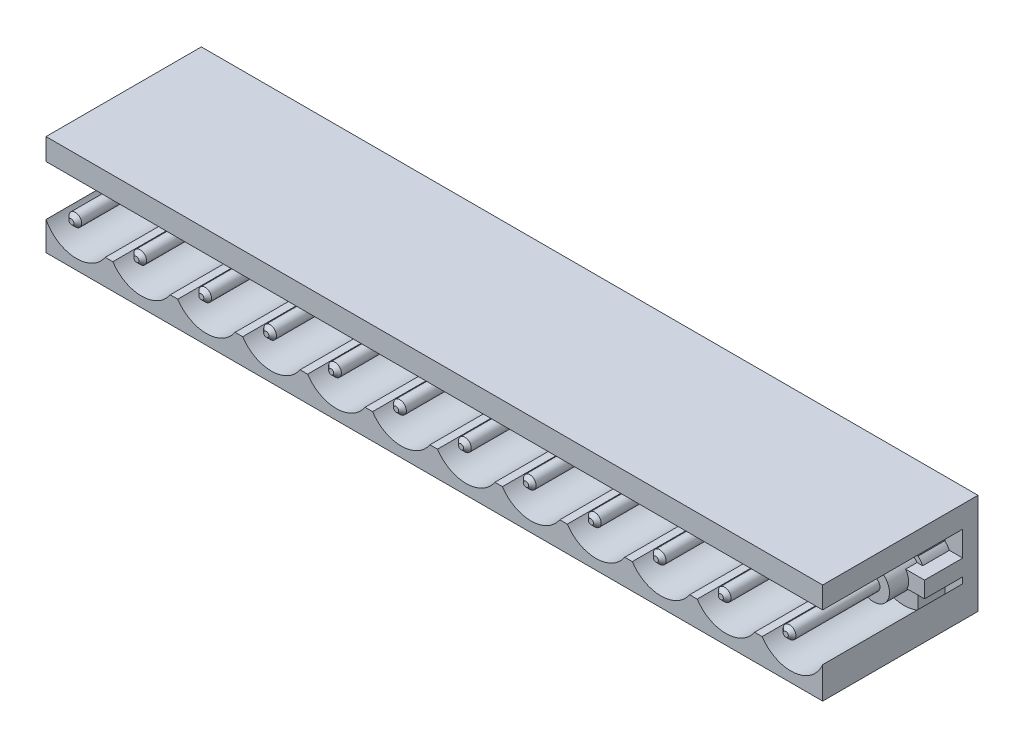
SolidWorks part; units mm, degrees
ref_plane "Front Plane" through (0, 0, 0) normal (0, 0, 1) x (1, 0, 0)
ref_plane "Top Plane" through (0, 0, 0) normal (0, 1, 0) x (1, 0, 0)
ref_plane "Right Plane" through (0, 0, 0) normal (1, 0, 0) x (0, 0, -1)
sketch "Sketch1" plane through (0, 0, 0) normal (1, 0, 0) x (0, 0, -1)
  line L1 (-6.1, 3.95) -> (6.1, 3.95)
  line L2 (-6.1, 3.95) -> (-6.1, -3.95)
  line L3 (-6.1, -3.95) -> (6.1, -3.95)
  line L4 (6.1, 3.95) -> (6.1, -3.95)
  line L5 (-6.1, 3.95) -> (6.1, -3.95) construction
  line L6 (-6.1, -3.95) -> (6.1, 3.95) construction
  point P0 (0, 0)
  dimension "D1" = 12.2
  dimension "D2" = 7.9
extrude "Boss-Extrude1" add sketch "Sketch1" along normal mid plane 61
sketch "Sketch2" plane through (0, 0, 6.1) normal (0, 0, 1) x (1, 0, 0)
  line L0 (30.5, -3.95) -> (-30.5, -3.95) construction
  line L1 (30.5, 3.95) -> (30.5, -3.95) construction
  line L2 (30.5, 3.95) -> (-30.5, 3.95) construction
  line L5 (25.3, 2.25) -> (30.7, 2.25)
  line L6 (30.7, -0.45) -> (30.7, 2.25)
  line L8 (20.2, 2.25) -> (25.6, 2.25)
  line L11 (15.1, 2.25) -> (20.5, 2.25)
  line L14 (10, 2.25) -> (15.4, 2.25)
  line L17 (4.9, 2.25) -> (10.3, 2.25)
  line L20 (-0.2, 2.25) -> (5.2, 2.25)
  line L23 (-5.3, 2.25) -> (0.1, 2.25)
  line L26 (-10.4, 2.25) -> (-5, 2.25)
  line L29 (-15.5, 2.25) -> (-10.1, 2.25)
  line L32 (-20.6, 2.25) -> (-15.2, 2.25)
  line L35 (-25.7, 2.25) -> (-20.3, 2.25)
  line L37 (-30.8, -0.45) -> (-30.8, 2.25)
  line L38 (-30.8, 2.25) -> (-25.4, 2.25)
  line L40 (-25.8467, -1.9375) -> (-25.2533, -1.9375)
  line L41 (-25.4, -0.45) -> (-25.4, 2.25) [skipped]
  line L42 (-20.7467, -1.9375) -> (-20.1533, -1.9375)
  line L43 (-20.3, -0.45) -> (-20.3, 2.25) [skipped]
  line L44 (-15.6467, -1.9375) -> (-15.0533, -1.9375)
  line L45 (-15.2, -0.45) -> (-15.2, 2.25) [skipped]
  line L46 (-10.5467, -1.9375) -> (-9.9533, -1.9375)
  line L47 (-10.1, -0.45) -> (-10.1, 2.25) [skipped]
  line L48 (-5.4467, -1.9375) -> (-4.8533, -1.9375)
  line L49 (20.5, -0.45) -> (20.5, 2.25) [skipped]
  line L50 (25.6, -0.45) -> (25.6, 2.25) [skipped]
  line L51 (15.4, -0.45) -> (15.4, 2.25) [skipped]
  line L52 (0.1, -0.45) -> (0.1, 2.25) [skipped]
  line L53 (5.2, -0.45) -> (5.2, 2.25) [skipped]
  line L54 (10.3, -0.45) -> (10.3, 2.25) [skipped]
  line L55 (-5, -0.45) -> (-5, 2.25) [skipped]
  line L56 (-0.3467, -1.9375) -> (0.2467, -1.9375)
  line L57 (4.7533, -1.9375) -> (5.3467, -1.9375)
  line L58 (9.8533, -1.9375) -> (10.4467, -1.9375)
  line L59 (14.9533, -1.9375) -> (15.5467, -1.9375)
  line L60 (20.0533, -1.9375) -> (20.6467, -1.9375)
  line L61 (25.1533, -1.9375) -> (25.7467, -1.9375)
  arc A0 (25.7467, -1.9375) -> (30.7, -0.45) centre (28, -0.45) ccw
  arc A1 (20.6467, -1.9375) -> (25.1533, -1.9375) centre (22.9, -0.45) ccw
  arc A2 (15.5467, -1.9375) -> (20.0533, -1.9375) centre (17.8, -0.45) ccw
  arc A3 (10.4467, -1.9375) -> (14.9533, -1.9375) centre (12.7, -0.45) ccw
  arc A4 (5.3467, -1.9375) -> (9.8533, -1.9375) centre (7.6, -0.45) ccw
  arc A5 (0.2467, -1.9375) -> (4.7533, -1.9375) centre (2.5, -0.45) ccw
  arc A6 (-4.8533, -1.9375) -> (-0.3467, -1.9375) centre (-2.6, -0.45) ccw
  arc A7 (-9.9533, -1.9375) -> (-5.4467, -1.9375) centre (-7.7, -0.45) ccw
  arc A8 (-15.0533, -1.9375) -> (-10.5467, -1.9375) centre (-12.8, -0.45) ccw
  arc A9 (-20.1533, -1.9375) -> (-15.6467, -1.9375) centre (-17.9, -0.45) ccw
  arc A10 (-25.2533, -1.9375) -> (-20.7467, -1.9375) centre (-23, -0.45) ccw
  arc A11 (-30.8, -0.45) -> (-25.8467, -1.9375) centre (-28.1, -0.45) ccw
  line M6 (-30.5, 3.95) -> (-30.5, -3.95)
  line M8 (30.5, -3.95) -> (30.5, 3.95)
  dimension "D1" = 5.4
  dimension "D2" = 3.5
  dimension "D3" = 2.5
  dimension "D4" = 1.7
  dimension "D5" = 12
extrude "Cut-Extrude4" cut sketch "Sketch2" against normal blind 11 contours A11 A10 A9 A8 A7 A6 A5 A4 A3 A2 A1 A0 L5 L8 L11 L14 L17 L20 L23 L26 L29 L32 L35 L38 M6 M8
sketch "Sketch3" plane through (0, 0, -4.9) normal (0, 0, 1) x (1, 0, 0)
  line L0 (-29.1932, -1.656) -> (-29.1932, -3.4405)
  line L1 (-29.1932, 2.5405) -> (-27.0068, 2.5405)
  line L2 (-29.1932, 2.5405) -> (-29.1932, 0.756)
  line L3 (-29.1932, -3.4405) -> (-27.0068, -3.4405)
  line L4 (-27.0068, 2.5405) -> (-27.0068, 0.756)
  line L5 (-27.0068, -1.656) -> (-27.0068, -3.4405)
  line L6 (-24.0932, 2.5405) -> (-21.9068, 2.5405)
  line L7 (-21.9068, 2.5405) -> (-21.9068, 0.756)
  line L8 (-21.9068, -1.656) -> (-21.9068, -3.4405)
  line L9 (-24.0932, -3.4405) -> (-21.9068, -3.4405)
  line L10 (-24.0932, -1.656) -> (-24.0932, -3.4405)
  line L11 (-24.0932, 2.5405) -> (-24.0932, 0.756)
  line L12 (-18.9932, 2.5405) -> (-16.8068, 2.5405)
  line L13 (-16.8068, 2.5405) -> (-16.8068, 0.756)
  line L14 (-16.8068, -1.656) -> (-16.8068, -3.4405)
  line L15 (-18.9932, -3.4405) -> (-16.8068, -3.4405)
  line L16 (-18.9932, -1.656) -> (-18.9932, -3.4405)
  line L17 (-18.9932, 2.5405) -> (-18.9932, 0.756)
  line L18 (-13.8932, 2.5405) -> (-11.7068, 2.5405)
  line L19 (-11.7068, 2.5405) -> (-11.7068, 0.756)
  line L20 (-11.7068, -1.656) -> (-11.7068, -3.4405)
  line L21 (-13.8932, -3.4405) -> (-11.7068, -3.4405)
  line L22 (-13.8932, -1.656) -> (-13.8932, -3.4405)
  line L23 (-13.8932, 2.5405) -> (-13.8932, 0.756)
  line L24 (-8.7932, 2.5405) -> (-6.6068, 2.5405)
  line L25 (-6.6068, 2.5405) -> (-6.6068, 0.756)
  line L26 (-6.6068, -1.656) -> (-6.6068, -3.4405)
  line L27 (-8.7932, -3.4405) -> (-6.6068, -3.4405)
  line L28 (-8.7932, -1.656) -> (-8.7932, -3.4405)
  line L29 (-8.7932, 2.5405) -> (-8.7932, 0.756)
  line L30 (-3.6932, 2.5405) -> (-1.5068, 2.5405)
  line L31 (-1.5068, 2.5405) -> (-1.5068, 0.756)
  line L32 (-1.5068, -1.656) -> (-1.5068, -3.4405)
  line L33 (-3.6932, -3.4405) -> (-1.5068, -3.4405)
  line L34 (-3.6932, -1.656) -> (-3.6932, -3.4405)
  line L35 (-3.6932, 2.5405) -> (-3.6932, 0.756)
  line L36 (1.4068, 2.5405) -> (3.5932, 2.5405)
  line L37 (3.5932, 2.5405) -> (3.5932, 0.756)
  line L38 (3.5932, -1.656) -> (3.5932, -3.4405)
  line L39 (1.4068, -3.4405) -> (3.5932, -3.4405)
  line L40 (1.4068, -1.656) -> (1.4068, -3.4405)
  line L41 (1.4068, 2.5405) -> (1.4068, 0.756)
  line L42 (6.5068, 2.5405) -> (8.6932, 2.5405)
  line L43 (8.6932, 2.5405) -> (8.6932, 0.756)
  line L44 (8.6932, -1.656) -> (8.6932, -3.4405)
  line L45 (6.5068, -3.4405) -> (8.6932, -3.4405)
  line L46 (6.5068, -1.656) -> (6.5068, -3.4405)
  line L47 (6.5068, 2.5405) -> (6.5068, 0.756)
  line L48 (11.6068, 2.5405) -> (13.7932, 2.5405)
  line L49 (13.7932, 2.5405) -> (13.7932, 0.756)
  line L50 (13.7932, -1.656) -> (13.7932, -3.4405)
  line L51 (11.6068, -3.4405) -> (13.7932, -3.4405)
  line L52 (11.6068, -1.656) -> (11.6068, -3.4405)
  line L53 (11.6068, 2.5405) -> (11.6068, 0.756)
  line L54 (16.7068, 2.5405) -> (18.8932, 2.5405)
  line L55 (18.8932, 2.5405) -> (18.8932, 0.756)
  line L56 (18.8932, -1.656) -> (18.8932, -3.4405)
  line L57 (16.7068, -3.4405) -> (18.8932, -3.4405)
  line L58 (16.7068, -1.656) -> (16.7068, -3.4405)
  line L59 (16.7068, 2.5405) -> (16.7068, 0.756)
  line L60 (21.8068, 2.5405) -> (23.9932, 2.5405)
  line L61 (23.9932, 2.5405) -> (23.9932, 0.756)
  line L62 (23.9932, -1.656) -> (23.9932, -3.4405)
  line L63 (21.8068, -3.4405) -> (23.9932, -3.4405)
  line L64 (21.8068, -1.656) -> (21.8068, -3.4405)
  line L65 (21.8068, 2.5405) -> (21.8068, 0.756)
  line L66 (26.9068, 2.5405) -> (29.0932, 2.5405)
  line L67 (29.0932, 2.5405) -> (29.0932, 0.756)
  line L68 (29.0932, -1.656) -> (29.0932, -3.4405)
  line L69 (26.9068, -3.4405) -> (29.0932, -3.4405)
  line L70 (26.9068, -1.656) -> (26.9068, -3.4405)
  line L71 (26.9068, 2.5405) -> (26.9068, 0.756)
  arc A0 (-29.1932, 0.756) -> (-29.1932, -1.656) centre (-28.1, -0.45) ccw
  arc A1 (-27.0068, -1.656) -> (-27.0068, 0.756) centre (-28.1, -0.45) ccw
  arc A2 (-21.9068, -1.656) -> (-21.9068, 0.756) centre (-23, -0.45) ccw
  arc A3 (-24.0932, 0.756) -> (-24.0932, -1.656) centre (-23, -0.45) ccw
  arc A4 (-16.8068, -1.656) -> (-16.8068, 0.756) centre (-17.9, -0.45) ccw
  arc A5 (-18.9932, 0.756) -> (-18.9932, -1.656) centre (-17.9, -0.45) ccw
  arc A6 (-11.7068, -1.656) -> (-11.7068, 0.756) centre (-12.8, -0.45) ccw
  arc A7 (-13.8932, 0.756) -> (-13.8932, -1.656) centre (-12.8, -0.45) ccw
  arc A8 (-6.6068, -1.656) -> (-6.6068, 0.756) centre (-7.7, -0.45) ccw
  arc A9 (-8.7932, 0.756) -> (-8.7932, -1.656) centre (-7.7, -0.45) ccw
  arc A10 (-1.5068, -1.656) -> (-1.5068, 0.756) centre (-2.6, -0.45) ccw
  arc A11 (-3.6932, 0.756) -> (-3.6932, -1.656) centre (-2.6, -0.45) ccw
  arc A12 (3.5932, -1.656) -> (3.5932, 0.756) centre (2.5, -0.45) ccw
  arc A13 (1.4068, 0.756) -> (1.4068, -1.656) centre (2.5, -0.45) ccw
  arc A14 (8.6932, -1.656) -> (8.6932, 0.756) centre (7.6, -0.45) ccw
  arc A15 (6.5068, 0.756) -> (6.5068, -1.656) centre (7.6, -0.45) ccw
  arc A16 (13.7932, -1.656) -> (13.7932, 0.756) centre (12.7, -0.45) ccw
  arc A17 (11.6068, 0.756) -> (11.6068, -1.656) centre (12.7, -0.45) ccw
  arc A18 (18.8932, -1.656) -> (18.8932, 0.756) centre (17.8, -0.45) ccw
  arc A19 (16.7068, 0.756) -> (16.7068, -1.656) centre (17.8, -0.45) ccw
  arc A20 (23.9932, -1.656) -> (23.9932, 0.756) centre (22.9, -0.45) ccw
  arc A21 (21.8068, 0.756) -> (21.8068, -1.656) centre (22.9, -0.45) ccw
  arc A22 (29.0932, -1.656) -> (29.0932, 0.756) centre (28, -0.45) ccw
  arc A23 (26.9068, 0.756) -> (26.9068, -1.656) centre (28, -0.45) ccw
  dimension "D1" = 12
extrude "Boss-Extrude2" add sketch "Sketch3" along normal blind 2.1
sketch "Sketch4" plane through (0, 0, -4.9) normal (0, 0, 1) x (1, 0, 0)
  line L0 (-30.5, 2.25) -> (-30.5, -1.6869) construction
  line L1 (-30.5, 0.2815) -> (30.5, 0.2815)
  line L2 (-30.5, 0.2815) -> (-30.5, -0.9954)
  line L3 (-30.5, -0.9954) -> (30.5, -0.9954)
  line L4 (30.5, 0.2815) -> (30.5, -0.9954)
  line L5 (30.5, -1.4698) -> (30.5, 2.25) construction
  point P8 (-30.5, -0.3569)
extrude "Boss-Extrude3" add sketch "Sketch4" along normal blind 3
sketch "Sketch6" plane through (0, 0, -4.9) normal (0, 0, 1) x (1, 0, 0)
  circle A0 centre (-28.1, -0.45) radius 1.25
  circle A1 centre (-23, -0.45) radius 1.25
  circle A2 centre (-17.9, -0.45) radius 1.25
  circle A3 centre (-12.8, -0.45) radius 1.25
  circle A4 centre (-7.7, -0.45) radius 1.25
  circle A5 centre (-2.6, -0.45) radius 1.25
  circle A6 centre (2.5, -0.45) radius 1.25
  circle A7 centre (7.6, -0.45) radius 1.25
  circle A8 centre (12.7, -0.45) radius 1.25
  circle A9 centre (17.8, -0.45) radius 1.25
  circle A10 centre (22.9, -0.45) radius 1.25
  circle A11 centre (28, -0.45) radius 1.25
  dimension "D2" = 2.5
  dimension "D1" = 12
extrude "Boss-Extrude4" add sketch "Sketch6" along normal blind 4.5
sketch "Sketch7" plane through (0, 0, -0.4) normal (0, 0, 1) x (1, 0, 0)
  circle A0 centre (-28.1, -0.45) radius 0.5
  dimension "D1" = 1
extrude "Boss-Extrude5" add sketch "Sketch7" along normal blind 6.9
chamfer "Chamfer1" distance 0.3 angle 45 1 edges at (-27.6, -0.45, 6.5)
pattern_linear "LPattern2" count 12 spacing 5.1 along (1, 0, 0) of "Boss-Extrude5", "Chamfer1"
